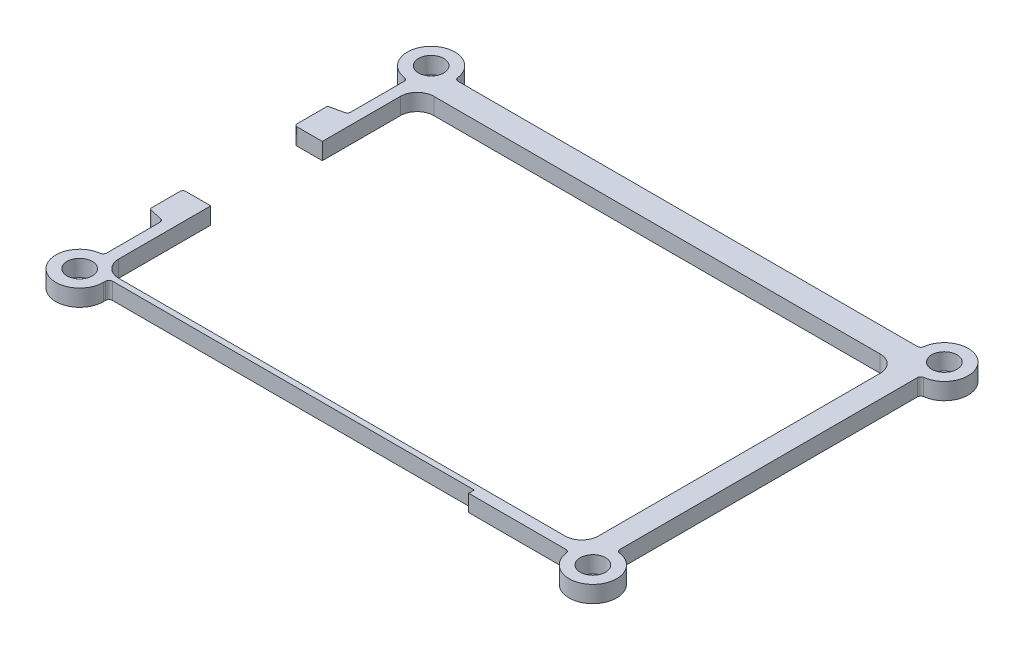
SolidWorks part; units mm, degrees
material "Balsa"
ref_plane "Front Plane" through (0, 0, 0) normal (0, 0, 1) x (1, 0, 0)
ref_plane "Top Plane" through (0, 0, 0) normal (0, 1, 0) x (1, 0, 0)
ref_plane "Right Plane" through (0, 0, 0) normal (1, 0, 0) x (0, 0, -1)
sketch "Sketch1" plane through (0, 0, 0) normal (0, 1, 0) x (1, 0, 0)
  line L0 (46, 0) -> (46, -63) construction
  line L5 (4.265, 0) -> (87.735, 0)
  line L6 (3.2, -3.25) -> (88.8, -3.25) construction
  line L7 (3.2, -3.25) -> (3.2, -59.75) construction
  line L8 (3.2, -59.75) -> (88.8, -59.75) construction
  line L9 (88.8, -3.25) -> (88.8, -59.75) construction
  line L10 (3.2, -3.25) -> (88.8, -59.75) construction
  line L11 (3.2, -59.75) -> (88.8, -3.25) construction
  line L12 (0, -4.265) -> (0, -58.735)
  line L14 (92, -4.265) -> (92, -58.735)
  line L15 (4.265, -63) -> (87.735, -63)
  circle A0 centre (0, 0) radius 2.265
  circle A1 centre (92, 0) radius 2.265
  circle A2 centre (92, -63) radius 2.265
  circle A3 centre (0, -63) radius 2.265
  arc A4 (4.265, 0) -> (0, -4.265) centre (0, 0) ccw
  arc A5 (92, -4.265) -> (87.735, 0) centre (92, 0) ccw
  arc A6 (87.735, -63) -> (92, -58.735) centre (92, -63) ccw
  arc A7 (0, -58.735) -> (4.265, -63) centre (0, -63) ccw
  point P7 (46, -31.5)
  dimension "D5" = 4.53
  dimension "D6" = 2
  dimension "D1" = 92
  dimension "D2" = 63
  dimension "D3" = 85.6
  dimension "D4" = 56.5
extrude "Boss-Extrude1" add sketch "Sketch1" along normal blind 3
sketch "Sketch2" plane through (0, 3, 0) normal (0, 1, 0) x (1, 0, 0)
  line L0 (0, -31.5) -> (92, -31.5) construction
  line L1 (0, -4.265) -> (0, -58.735) construction
  line L2 (92, -58.735) -> (92, -4.265) construction
  line L4 (0, -21.5) -> (6.5, -21.5)
  line L5 (0, -21.5) -> (0, -41.5)
  line L6 (0, -41.5) -> (6.5, -41.5)
  line L7 (6.5, -21.5) -> (6.5, -41.5)
  point P11 (0, -31.5)
  dimension "D1" = 6.5
  dimension "D2" = 20
extrude "Cut-Extrude1" cut sketch "Sketch2" against normal blind 3
sketch "Sketch3" plane through (0, 3, 0) normal (0, 1, 0) x (1, 0, 0)
  line L0 (0, -14.9) -> (-2.7, -15.5)
  line L1 (0, -21.5) -> (-2.5, -21.5)
  line L2 (0, -21.5) -> (0, -14.9)
  line L4 (-3, -21) -> (-3, -15.8)
  line L5 (6.5, -31.5) -> (-15.1716, -31.5) construction
  line L6 (6.5, -41.5) -> (6.5, -21.5) construction
  line L7 (0, -41.5) -> (0, -48.1)
  line L8 (0, -41.5) -> (-2.5, -41.5)
  line L9 (-3, -42) -> (-3, -47.2)
  line L10 (0, -48.1) -> (-2.7, -47.5)
  arc A0 (-2.5, -21.5) -> (-3, -21) centre (-2.5, -21) cw
  arc A1 (-3, -15.8) -> (-2.7, -15.5) centre (-2.7, -15.8) cw
  arc A2 (-2.5, -41.5) -> (-3, -42) centre (-2.5, -42) ccw
  arc A3 (-3, -47.2) -> (-2.7, -47.5) centre (-2.7, -47.2) ccw
  point P7 (-3, -21.5)
  point P10 (-3, -15.5)
  dimension "D3" = 0.5
  dimension "D4" = 0.3
  dimension "D1" = 3
  dimension "D2" = 6
  dimension "D5" = 6.6
extrude "Boss-Extrude2" add sketch "Sketch3" against normal blind 3
sketch "Sketch8" plane through (0, 3, 0) normal (0, 1, 0) x (1, 0, 0)
  line L0 (45, -4.5) -> (45, -61) construction
  line L2 (4.265, -63) -> (87.735, -63) construction
  line L3 (0, -4.265) -> (0, -14.9) construction
  line L4 (5, -4.5) -> (85, -4.5)
  line L5 (2, -7.5) -> (2, -58)
  line L6 (5, -61) -> (85, -61)
  line L7 (88, -7.5) -> (88, -58)
  line L8 (2, -4.5) -> (88, -61) construction
  line L9 (2, -61) -> (88, -4.5) construction
  line L10 (87.735, 0) -> (4.265, 0) construction
  line L11 (92, -58.735) -> (92, -4.265) construction
  arc A0 (85, -61) -> (88, -58) centre (85, -58) ccw
  arc A1 (88, -7.5) -> (85, -4.5) centre (85, -7.5) ccw
  arc A2 (5, -4.5) -> (2, -7.5) centre (5, -7.5) ccw
  arc A3 (5, -61) -> (2, -58) centre (5, -58) cw
  point P6 (45, -32.75)
  dimension "D5" = 3
  dimension "D1" = 2
  dimension "D2" = 2
  dimension "D3" = 4.5
  dimension "D4" = 4
extrude "Cut-Extrude5" cut sketch "Sketch8" against normal blind 17
sketch "Sketch9" plane through (0, 3, 0) normal (0, 1, 0) x (1, 0, 0)
  line L1 (4.265, -63) -> (69.735, -63)
  line L2 (4.265, -63) -> (4.265, -62)
  line L3 (4.265, -62) -> (69.735, -62)
  line L4 (69.735, -63) -> (69.735, -62)
  dimension "D1" = 1
  dimension "D2" = 18
extrude "Cut-Extrude6" cut sketch "Sketch9" against normal blind 17
fillet "Fillet2" radius 0.6 10 edges at (4.265, 1.5, 62) (0, 1.5, 58.735) (0, 1.5, 48.1) (0, 1.5, 14.9) (0, 1.5, 4.265) (4.265, 1.5, 0) (87.735, 1.5, 0) (92, 1.5, 4.265) (92, 1.5, 58.735) (87.735, 1.5, 63)
fillet "Fillet3" radius 0.1 1 edges at (69.735, 1.5, 62)
